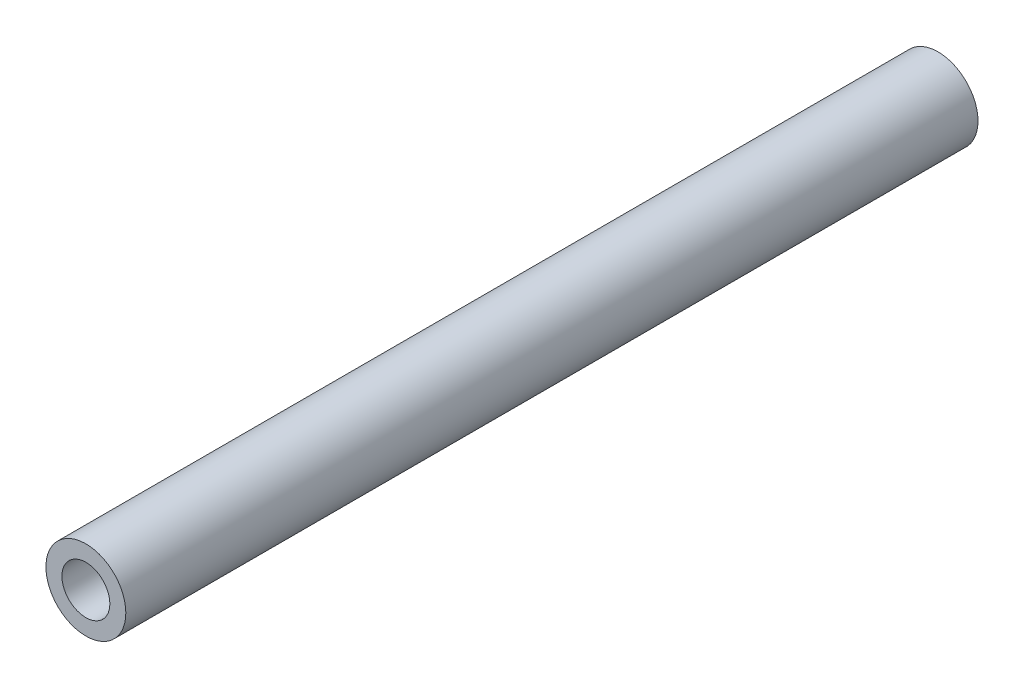
SolidWorks part; units mm, degrees
ref_plane "正面" through (0, 0, 0) normal (0, 0, 1) x (1, 0, 0)
ref_plane "平面" through (0, 0, 0) normal (0, 1, 0) x (1, 0, 0)
ref_plane "右側面" through (0, 0, 0) normal (1, 0, 0) x (0, 0, -1)
sketch "Sketch1" plane through (0, 0, 0) normal (0, 0, 1) x (1, 0, 0)
  circle A0 centre (0, 0) radius 1.5
  circle A1 centre (0, 0) radius 0.9
  dimension "D1" = 3
  dimension "D2" = 1.8
extrude "Boss-Extrude1" add sketch "Sketch1" along normal blind 32
